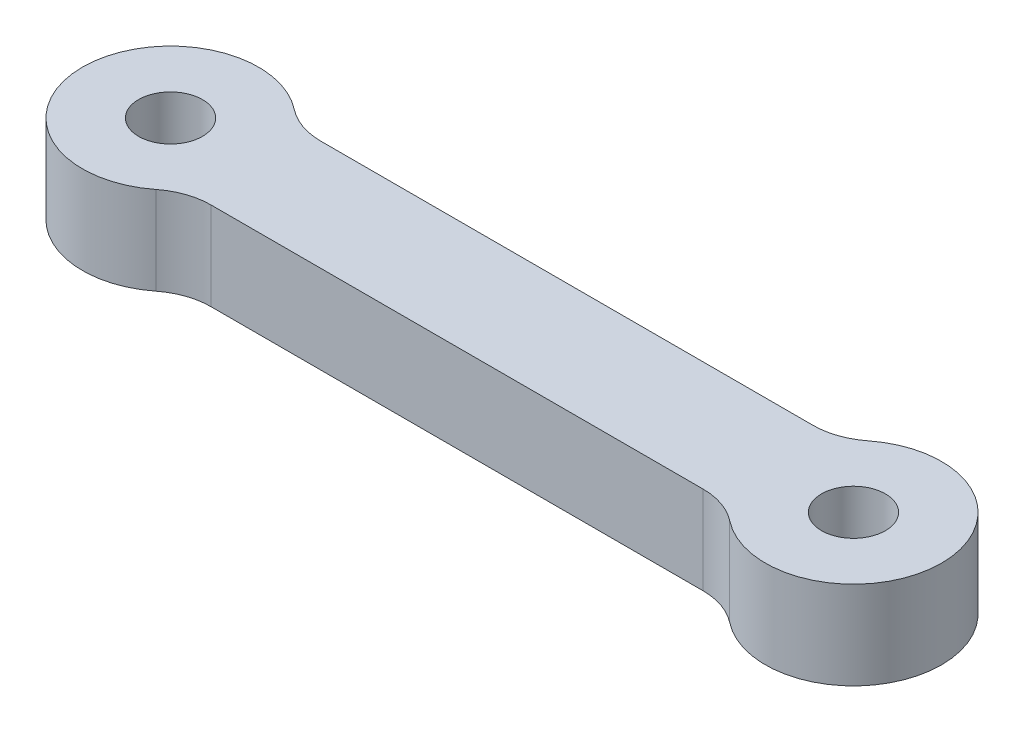
SolidWorks part; units mm, degrees
ref_plane "Front Plane" through (0, 0, 0) normal (0, 0, 1) x (1, 0, 0)
ref_plane "Top Plane" through (0, 0, 0) normal (0, 1, 0) x (1, 0, 0)
ref_plane "Right Plane" through (0, 0, 0) normal (1, 0, 0) x (0, 0, -1)
sketch "Sketch1" plane through (0, 0, 0) normal (0, 1, 0) x (1, 0, 0)
  line L0 (0, 0) -> (31, 0) construction
  line L1 (3.1225, 2.5) -> (27.8775, 2.5)
  line L2 (3.1225, -2.5) -> (27.8775, -2.5)
  circle A0 centre (0, 0) radius 4
  circle A1 centre (31, 0) radius 4
  circle A2 centre (0, 0) radius 1.45
  circle A3 centre (31, 0) radius 1.45
  dimension "D1" = 8
  dimension "D3" = 8
  dimension "D5" = 2.9
  dimension "D6" = 2.9
  dimension "D2" = 31
  dimension "D4" = 2.5
extrude "Boss-Extrude1" add sketch "Sketch1" along normal blind 4
fillet "Fillet1" radius 3 4 edges at (3.1225, 2, 2.5) (27.8775, 2, 2.5) (27.8775, 2, -2.5) (3.1225, 2, -2.5)
